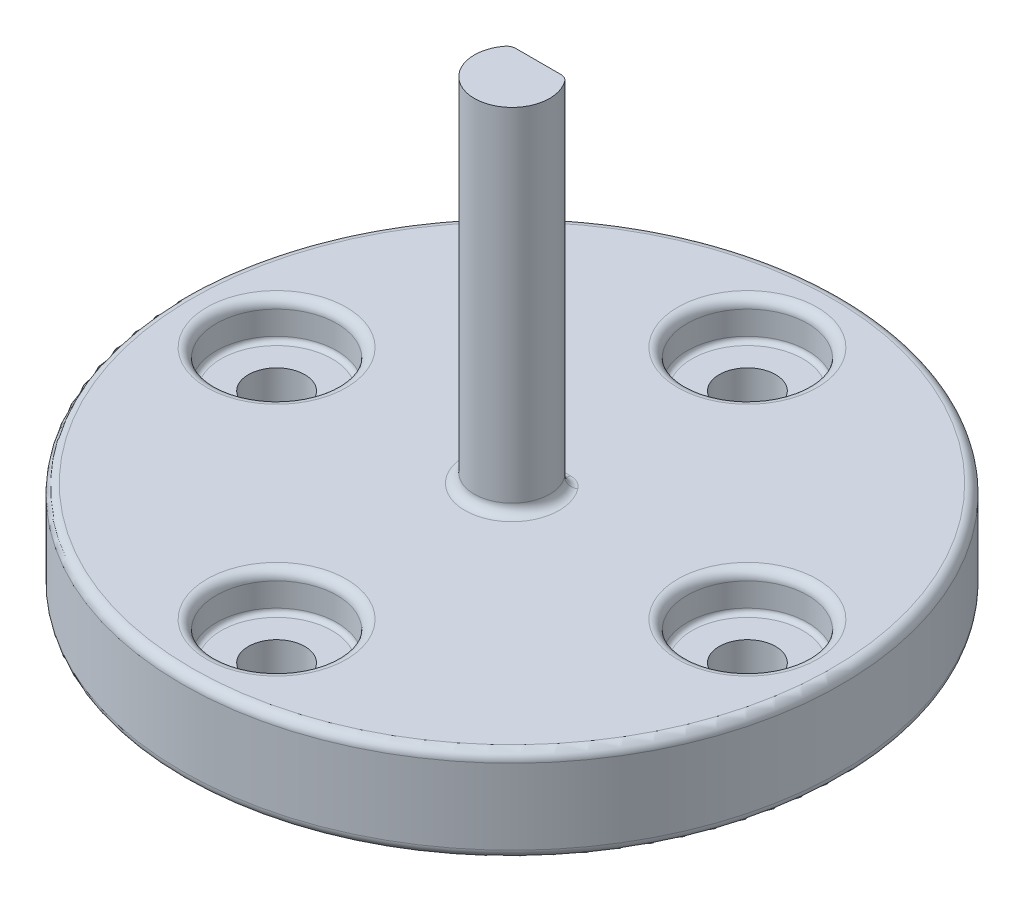
SolidWorks part; units mm, degrees
ref_plane "Front Plane" through (0, 0, 0) normal (0, 0, 1) x (1, 0, 0)
ref_plane "Top Plane" through (0, 0, 0) normal (0, 1, 0) x (1, 0, 0)
ref_plane "Right Plane" through (0, 0, 0) normal (1, 0, 0) x (0, 0, -1)
sketch "Sketch1" plane through (0, 0, 0) normal (0, 1, 0) x (1, 0, 0)
  line L0 (0, 0) -> (41.9723, 0) construction
  line L1 (41.9723, 0) -> (-40.3772, 0) construction
  line L2 (-30.1236, 1.4) -> (41.9723, 1.4) construction
  line L3 (0, 1.4) -> (41.9723, 1.4) construction
  line L5 (-1.4283, 1.4) -> (1.4283, 1.4)
  circle A0 centre (0, 0) radius 2 construction
  arc A2 (-1.4283, 1.4) -> (1.4283, 1.4) centre (0, 0) ccw
  dimension "D1" = 4
  dimension "D2" = 1.4
extrude "Boss-Extrude1" add sketch "Sketch1" along normal blind 18.7
fillet "Fillet1" radius 0.5 2 edges at (-1.4283, 9.35, -1.4) (1.4283, 9.35, -1.4)
sketch "Sketch2" plane through (0, 0, 0) normal (0, 1, 0) x (1, 0, 0)
  line L0 (0, 0) -> (-7.9491, 0) construction
  line L5 (-7.9491, 0) -> (8.8578, 0) construction
  line L6 (0, 0) -> (0, 5.3892) construction
  line L7 (0, 5.3892) -> (0, -6.4859) construction
  line L8 (0, 5) -> (-2.5, 5) construction
  line L9 (-2.5, 5) -> (3.5605, 5) construction
  line L10 (6, 0) -> (6, 4.7884) construction
  line L11 (6, 4.7884) -> (6, -5.905) construction
  line L12 (0, -5) -> (4.3483, -5) construction
  line L13 (4.3483, -5) -> (-5.4572, -5) construction
  line L14 (-6, 0) -> (-6, 3.5603) construction
  line L15 (-6, 3.5603) -> (-6, -6.8261) construction
  line L16 (2.5, 5) -> (2.5, 2.5) construction
  line L17 (2.5, 2.5) -> (6, 2.5) construction
  line L18 (6, -2.5) -> (2.5, -2.5) construction
  line L19 (2.5, -2.5) -> (2.5, -5) construction
  line L20 (-2.5, 5) -> (-2.5, 2.5) construction
  line L21 (-2.5, 2.5) -> (-6, 2.5) construction
  line L22 (-2.5, -5) -> (-2.5, -2.5) construction
  line L23 (-2.5, -2.5) -> (-6, -2.5) construction
  circle A0 centre (0, 5) radius 1.5 construction
  circle A1 centre (-6, 0) radius 1.5 construction
  circle A2 centre (6, 0) radius 1.5 construction
  circle A3 centre (0, -5) radius 1.5 construction
  circle A4 centre (0, 5) radius 2.5 construction
  circle A5 centre (-6, 0) radius 2.5 construction
  circle A6 centre (0, -5) radius 2.5 construction
  circle A7 centre (6, 0) radius 2.5 construction
  arc A8 (2.5, 5) -> (-2.5, 5) centre (0, 5) ccw construction
  arc A9 (6, -2.5) -> (6, 2.5) centre (6, 0) ccw construction
  arc A10 (2.5, -5) -> (-2.5, -5) centre (0, -5) cw construction
  arc A11 (-6, 2.5) -> (-6, -2.5) centre (-6, 0) ccw construction
  circle A12 centre (0, 0) radius 17.5
  circle A13 centre (0, 5) radius 4 construction
  circle A14 centre (6, 0) radius 4 construction
  point P0 (0, 0)
  dimension "D1" = 3
  dimension "D7" = 35
  dimension "D2" = 5
  dimension "D3" = 6
  dimension "D4" = 1
  dimension "D5" = 1.5
  dimension "D6" = 1.5
extrude "Boss-Extrude3" add sketch "Sketch2" against normal blind 5
sketch "Sketch3" plane through (0, -5, 0) normal (0, -1, 0) x (1, 0, 0)
  line L6 (0, 0) -> (-16.633, 0) construction
  line L7 (-16.633, 0) -> (19.5957, 0) construction
  line L8 (0, 0) -> (0, -13.6916) construction
  line L9 (0, -13.6916) -> (0, 14.9977) construction
  circle A3 centre (0, -5) radius 1.5 construction
  circle A4 centre (0, 12.5) radius 1.5
  circle A5 centre (12.5, 0) radius 1.5
  circle A6 centre (-12.5, 0) radius 1.5
  circle A12 centre (0, -12.5) radius 1.5
  dimension "D1" = 3
  dimension "D3" = 25
  dimension "D2" = 25
extrude "Cut-Extrude1" cut sketch "Sketch3" against normal through all both and the other way through all
sketch "Sketch4" plane through (0, 0, 0) normal (0, 1, 0) x (1, 0, 0)
  circle A12 centre (12.5, 0) radius 1.5 construction
  circle A13 centre (0, 12.5) radius 1.5 construction
  circle A14 centre (0, -12.5) radius 1.5 construction
  circle A15 centre (-12.5, 0) radius 1.5 construction
  circle A16 centre (12.5, 0) radius 1.5 construction
  circle A17 centre (0, 12.5) radius 1.5 construction
  circle A18 centre (0, -12.5) radius 1.5 construction
  circle A19 centre (-12.5, 0) radius 1.5 construction
  circle A20 centre (0, -12.5) radius 3.2
  circle A21 centre (0, 12.5) radius 3.2
  circle A22 centre (-12.5, 0) radius 3.2
  circle A23 centre (12.5, 0) radius 3.2
  dimension "D1" = 1.7
  dimension "D2" = 1.7
extrude "Cut-Extrude2" cut sketch "Sketch4" against normal offset from surface (2 mm away) 2 up to face at (0, 0, -11)
fillet "Fillet2" radius 0.5 4 edges at (0, 0, 15.7) (12.5, 0, 3.2) (0, 0, -9.3) (-12.5, 0, 3.2)
fillet "Fillet3" radius 0.25 4 edges at (12.5, -2, 3.2) (0, -2, 15.7) (0, -2, -9.3) (-12.5, -2, 3.2)
fillet "Fillet4" radius 0.5 2 edges at (0, -5, 17.5) (0, 0, 17.5)
fillet "Fillet5" radius 0.5 4 edges at (-1.4236, 0, -1.3472) (0, 0, -1.4) (1.4236, 0, -1.3472) (0, 0, 2)
